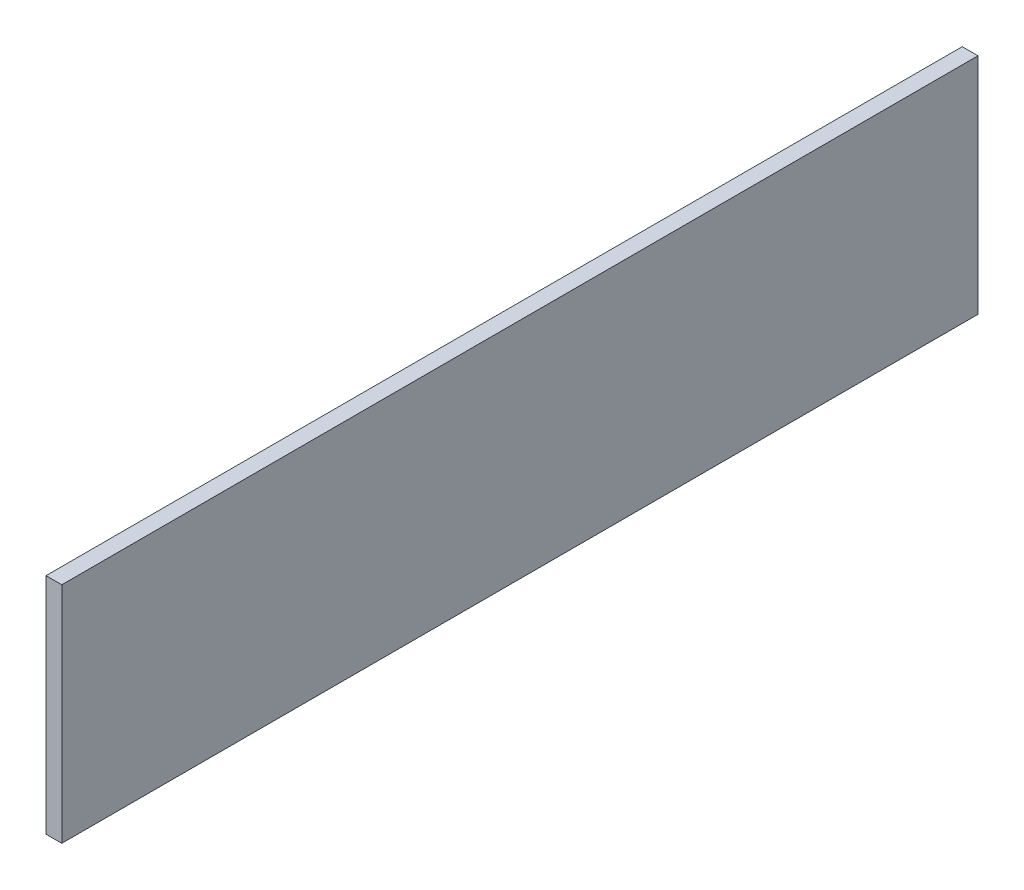
SolidWorks part; units mm, degrees
ref_plane "Alzado" through (0, 0, 0) normal (0, 0, 1) x (1, 0, 0)
ref_plane "Planta" through (0, 0, 0) normal (0, 1, 0) x (1, 0, 0)
ref_plane "Vista lateral" through (0, 0, 0) normal (1, 0, 0) x (0, 0, -1)
sketch "Croquis1" plane through (0, 0, 0) normal (1, 0, 0) x (0, 0, -1)
  line L1 (-42.2288, -26.219) -> (248.2712, -26.219)
  line L2 (-42.2288, -26.219) -> (-42.2288, 44.781)
  line L3 (-42.2288, 44.781) -> (248.2712, 44.781)
  line L4 (248.2712, -26.219) -> (248.2712, 44.781)
  dimension "D1" = 71
  dimension "D2" = 290.5
extrude "Saliente-Extruir1" add sketch "Croquis1" along normal blind 5
